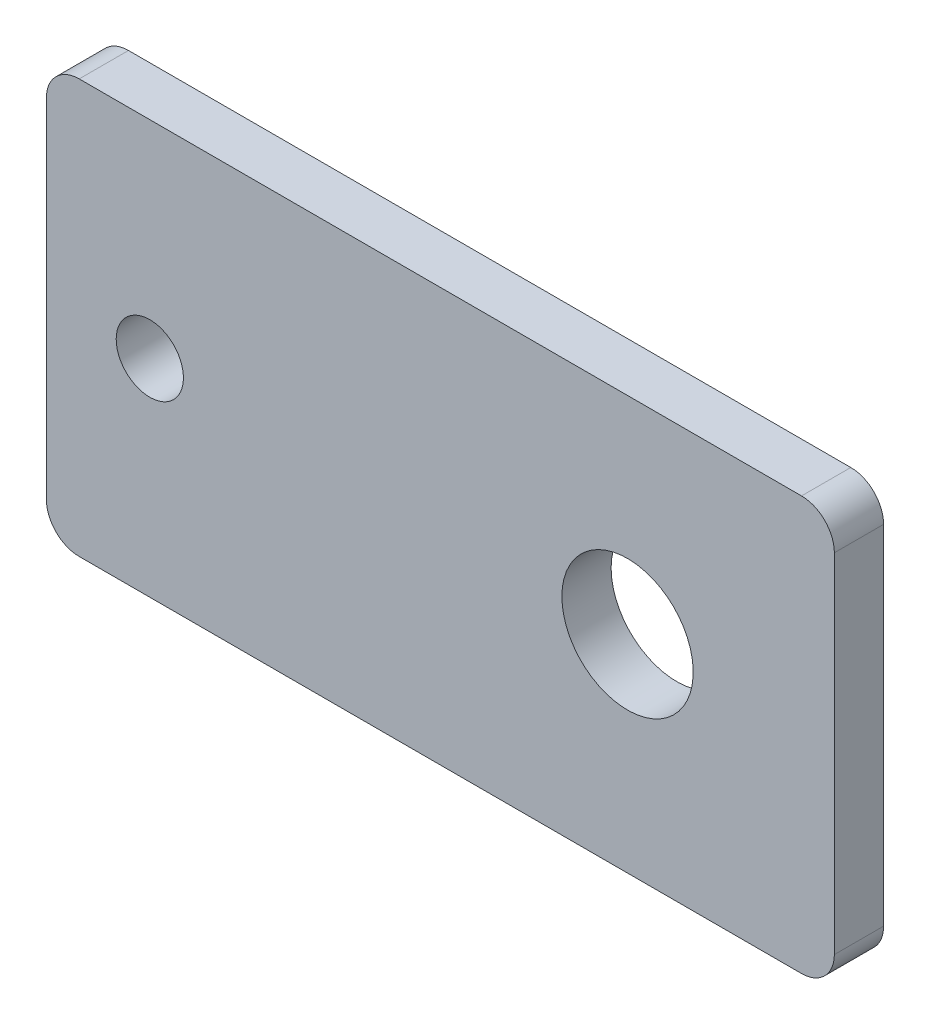
SolidWorks part; units mm, degrees
ref_plane "Front Plane" through (0, 0, 0) normal (0, 0, 1) x (1, 0, 0)
ref_plane "Top Plane" through (0, 0, 0) normal (0, 1, 0) x (1, 0, 0)
ref_plane "Right Plane" through (0, 0, 0) normal (1, 0, 0) x (0, 0, -1)
sketch "Sketch1" plane through (0, 0, 0) normal (0, 0, 1) x (1, 0, 0)
  line L1 (241.75, -38.1) -> (165.55, -38.1)
  line L2 (241.75, -38.1) -> (241.75, 1.9)
  line L3 (241.75, 1.9) -> (165.55, 1.9)
  line L4 (165.55, -38.1) -> (165.55, 1.9)
  circle A0 centre (221.75, -18.1) radius 6.35
  circle A1 centre (175.55, -18.1) radius 3.25
  dimension "D3" = 20
  dimension "D4" = 10
  dimension "D7" = 6.5
  dimension "D1" = 40
  dimension "D2" = 76.2
  dimension "D5" = 20
  dimension "D6" = 20
extrude "Boss-Extrude1" add sketch "Sketch1" along normal blind 4.7625
fillet "Fillet1" radius 3.175 4 edges at (165.55, 1.9, 2.3813) (165.55, -38.1, 2.3813) (241.75, -38.1, 2.3813) (241.75, 1.9, 2.3813)
